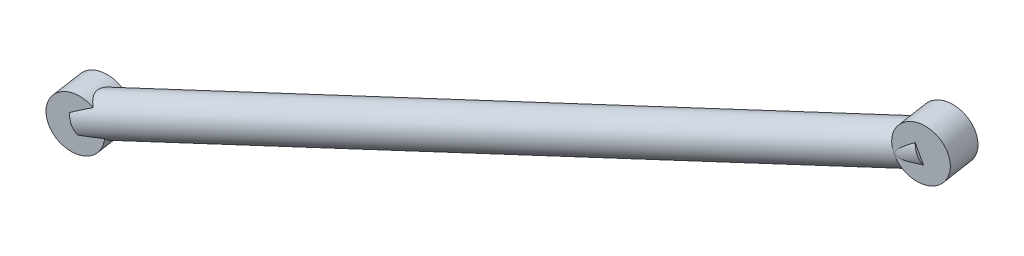
SolidWorks part; units mm, degrees
ref_plane "Plano frontal" through (0, 0, 0) normal (0, 0, 1) x (1, 0, 0)
ref_plane "Plano superior" through (0, 0, 0) normal (0, 1, 0) x (1, 0, 0)
ref_plane "Plano direito" through (0, 0, 0) normal (1, 0, 0) x (0, 0, -1)
sketch3d "SUSP_RR_toe_link_eixo"
  line L0 (175, 1319.6, -94) -> (520.81, 1474.2, -108.53)
sweep "SUSP_RR_toe_link" add path "SUSP_RR_toe_link_eixo" circular profile diameter 16 parameters "D3"=16
sketch3d "SUSP_RR_toe_link_rod_end_in_eixo"
  line L0 (176.0347, 1319.6, -87.0769) -> (173.9653, 1319.6, -100.9231)
sweep "SUSP_RR_toe_link_rod_end_in" add path "SUSP_RR_toe_link_rod_end_in_eixo" circular profile diameter 22 parameters "D3"=22
sketch3d "SUSP_RR_toe_link_rod_end_out_eixo"
  line L0 (521.8447, 1474.2, -101.6069) -> (519.7753, 1474.2, -115.4531)
sweep "SUSP_RR_toe_link_rod_end_out" add path "SUSP_RR_toe_link_rod_end_out_eixo" circular profile diameter 22 parameters "D3"=22
sketch3d "REF_SKETCH"
  line L0 (171, 1317.2, -95.8) -> (179, 1322, -92.2)
  line L1 (177.4, 1316.6, -97.2) -> (172.6, 1322.6, -90.8)
  line L2 (516.81, 1471.8, -110.33) -> (524.81, 1476.6, -106.73)
  line L3 (523.21, 1471.2, -111.73) -> (518.41, 1477.2, -105.33)
ref_point "P_IN"
ref_point "P_OUT"
